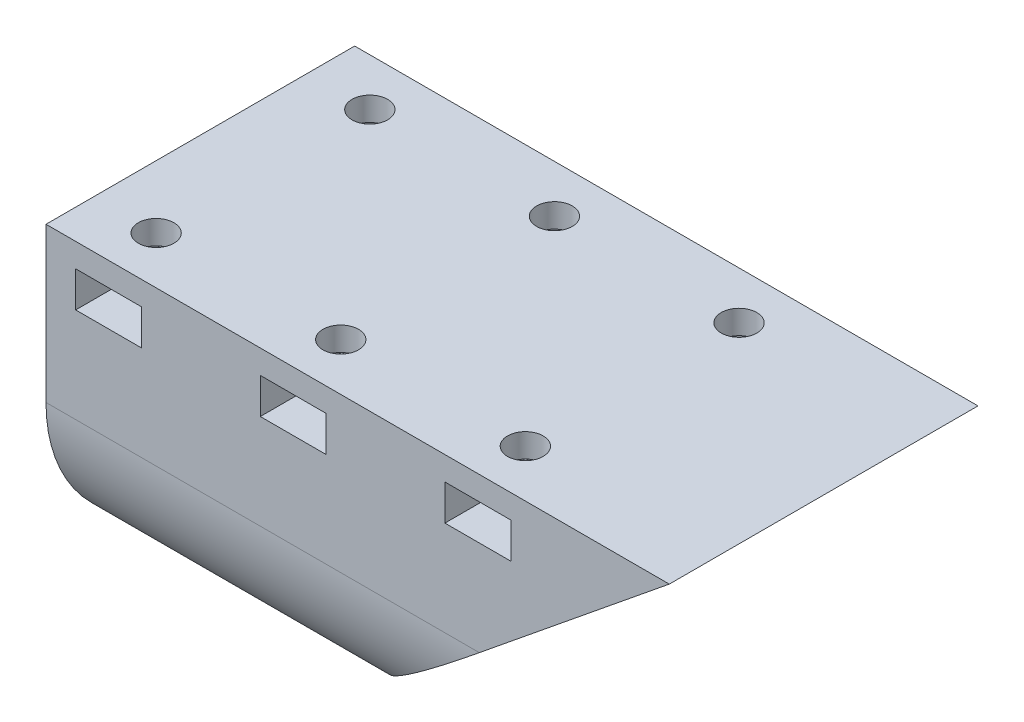
SolidWorks part; units mm, degrees
ref_plane "Front Plane" through (0, 0, 0) normal (0, 0, 1) x (1, 0, 0)
ref_plane "Top Plane" through (0, 0, 0) normal (0, 1, 0) x (1, 0, 0)
ref_plane "Right Plane" through (0, 0, 0) normal (1, 0, 0) x (0, 0, -1)
sketch "Sketch1" plane through (0, 0, 0) normal (1, 0, 0) x (0, 0, -1)
  line L0 (1.4916, 6.9937) -> (6.9937, 1.4916)
  line L1 (-6.9937, -1.4916) -> (-1.4916, -6.9937)
  line L2 (0, 0) -> (13, 0) construction
  circle A0 centre (0, 0) radius 13
  circle A1 centre (0, 9) radius 1
  circle A2 centre (9, 0) radius 1
  circle A3 centre (0, -9) radius 1
  circle A4 centre (-9, 0) radius 1
  arc A5 (-6.9937, -1.4916) -> (1.4916, 6.9937) centre (0, 0) cw
  arc A6 (6.9937, 1.4916) -> (-1.4916, -6.9937) centre (0, 0) cw
  point P14 (0, 0)
  dimension "D1" = 26
  dimension "D3" = 2
  dimension "D2" = 9
  dimension "D5" = 12
  dimension "D6" = 6
  dimension "D7" = 45
  dimension "D8" = 2.5
  dimension "D9" = 2.5
  dimension "D10" = 2.5
  dimension "D11" = 2.5
  dimension "D4" = 4
extrude "Boss-Extrude1" add sketch "Sketch1" along normal blind 2.5
sketch "Sketch2" plane through (2.5, 0, 0) normal (1, 0, 0) x (0, 0, -1)
  line L0 (-13, 13) -> (13, 13)
  line L4 (13, 13) -> (13, 0)
  line L5 (-13, 0) -> (-13, 13)
  circle A1 centre (0, 0) radius 11.25
  arc A2 (13, 0) -> (-13, 0) centre (0, 0) cw
  point P6 (0, 13)
  dimension "D1" = 22.5
  dimension "D2" = 13
  dimension "D3" = 26
extrude "Boss-Extrude2" add sketch "Sketch2" along normal blind 50 and the other way up to surface other way up to face at (0, 0, -10)
sketch "Sketch3" plane through (0, 0, 0) normal (0, 0, 1) x (1, 0, 0)
  line L0 (52.5, 13) -> (20.5, -13)
  line L4 (20.5, -13) -> (52.5, -13)
  line L5 (52.5, -13) -> (52.5, 13)
  line L8 (0, -13) -> (52.5, -13) construction
  dimension "D2" = 20.5
extrude "Cut-Extrude1" cut sketch "Sketch3" against normal through all both and the other way through all
sketch "Sketch4" plane through (0, 0, 13) normal (0, 0, 1) x (1, 0, 0)
  line L1 (2.5, 11) -> (8.05, 11)
  line L2 (2.5, 11) -> (2.5, 8)
  line L3 (2.5, 8) -> (8.05, 8)
  line L4 (8.05, 11) -> (8.05, 8)
  line L5 (18.05, 11) -> (23.6, 11)
  line L6 (18.05, 11) -> (18.05, 8)
  line L7 (18.05, 8) -> (23.6, 8)
  line L8 (23.6, 11) -> (23.6, 8)
  line L9 (33.6, 11) -> (39.15, 11)
  line L10 (33.6, 11) -> (33.6, 8)
  line L11 (33.6, 8) -> (39.15, 8)
  line L12 (39.15, 11) -> (39.15, 8)
  line L14 (0, 0) -> (0, 13) construction
  dimension "D1" = 5.55
  dimension "D2" = 3
  dimension "D3" = 2.5
  dimension "D4" = 8
  dimension "D5" = 10
  dimension "D6" = 10
extrude "Cut-Extrude2" cut sketch "Sketch4" against normal blind 6.75
sketch "Sketch5" plane through (0, 13, 0) normal (0, 1, 0) x (1, 0, 0)
  line L0 (0, -13) -> (0, 13) construction
  circle A0 centre (5.275, -9) radius 1.5
  circle A1 centre (20.825, -9) radius 1.5
  circle A2 centre (36.375, -9) radius 1.5
  dimension "D1" = 3
  dimension "D2" = 15.55
  dimension "D3" = 15.55
  dimension "D4" = 9
  dimension "D5" = 5.275
extrude "Cut-Extrude3" cut sketch "Sketch5" against normal up to surface (5 mm away) up to face at (20.825, 8, 10.4548)
mirror "Mirror1" about plane through (0, 0, 0) normal (0, 0, 1) of "Cut-Extrude2", "Cut-Extrude3"
sketch "Sketch7" plane through (0, 0, 0) normal (-1, 0, 0) x (0, 0, 1)
  line L0 (6.9937, -1.4916) -> (1.4916, -6.9937) construction
  line L1 (-1.4916, 6.9937) -> (-6.9937, 1.4916) construction
  line L2 (6.9937, -1.4916) -> (1.4916, -6.9937)
  line L3 (13, 0) -> (13, 13)
  line L4 (13, 13) -> (-13, 13)
  line L5 (-13, 13) -> (-13, 0)
  line L6 (13, 0) -> (13, 13)
  line L7 (13, 13) -> (-13, 13)
  line L8 (-13, 13) -> (-13, 0)
  line L9 (-1.4916, 6.9937) -> (-6.9937, 1.4916)
  circle A0 centre (0, -9) radius 1 construction
  arc A1 (-13, 0) -> (13, 0) centre (0, 0) ccw
  arc A2 (-13, 0) -> (13, 0) centre (0, 0) ccw
  circle A3 centre (-9, 0) radius 1 construction
  arc A4 (-6.9937, 1.4916) -> (1.4916, -6.9937) centre (0, 0) ccw construction
  circle A5 centre (9, 0) radius 1 construction
  circle A6 centre (0, 9) radius 1 construction
  arc A7 (6.9937, -1.4916) -> (-1.4916, 6.9937) centre (0, 0) ccw construction
  circle A8 centre (0, -9) radius 1
  circle A9 centre (-9, 0) radius 1
  arc A10 (-6.9937, 1.4916) -> (1.4916, -6.9937) centre (0, 0) ccw
  circle A11 centre (9, 0) radius 1
  circle A12 centre (0, 9) radius 1
  arc A13 (6.9937, -1.4916) -> (-1.4916, 6.9937) centre (0, 0) ccw
  dimension "D1" = 0
